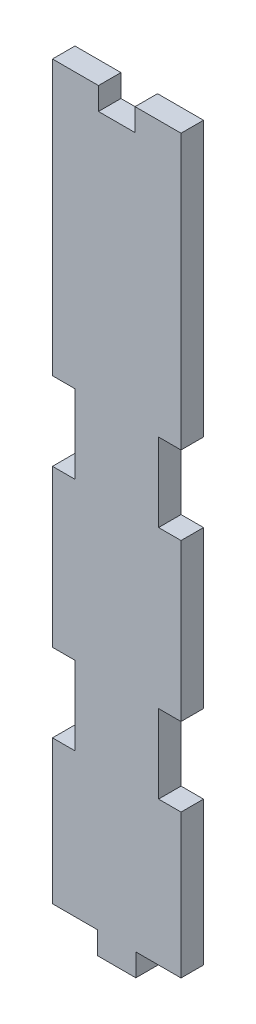
SolidWorks part; units mm, degrees
ref_plane "Front Plane" through (0, 0, 0) normal (0, 0, 1) x (1, 0, 0)
ref_plane "Top Plane" through (0, 0, 0) normal (0, 1, 0) x (1, 0, 0)
ref_plane "Right Plane" through (0, 0, 0) normal (1, 0, 0) x (0, 0, -1)
sketch "Sketch1" plane through (0, 0, 0) normal (0, 0, 1) x (1, 0, 0)
  line L0 (3.5, 70) -> (12.3, 70)
  line L1 (-12.3, -70) -> (-3.65, -70)
  line L2 (-12.3, -70) -> (-12.3, -42.5)
  line L3 (-12.3, 70) -> (-3.5, 70)
  line L4 (12.3, -70) -> (12.3, -42.5)
  line L5 (-12.3, -70) -> (12.3, 70) construction
  line L6 (-12.3, 70) -> (12.3, -70) construction
  line L8 (-3.5, 70) -> (-3.5, 65.7)
  line L9 (-3.5, 65.7) -> (3.5, 65.7)
  line L10 (3.5, 70) -> (3.5, 65.7)
  line L11 (3.65, -70) -> (12.3, -70)
  line L13 (-3.65, -70) -> (-3.65, -74.3)
  line L14 (-3.65, -74.3) -> (3.65, -74.3)
  line L15 (3.65, -70) -> (3.65, -74.3)
  line L16 (0, -74.3) -> (0, 65.7) construction
  line L17 (12.3, -27.5) -> (12.3, 2.5)
  line L18 (12.3, -27.5) -> (8, -27.5)
  line L20 (12.3, -42.5) -> (8, -42.5)
  line L21 (8, -27.5) -> (8, -42.5)
  line L22 (12.3, 17.5) -> (8, 17.5)
  line L24 (12.3, 2.5) -> (8, 2.5)
  line L25 (8, 17.5) -> (8, 2.5)
  line L26 (12.3, 17.5) -> (12.3, 70)
  line L27 (-8, 17.5) -> (-8, 2.5)
  line L28 (-12.3, 2.5) -> (-8, 2.5)
  line L29 (-12.3, 17.5) -> (-8, 17.5)
  line L30 (-8, -27.5) -> (-8, -42.5)
  line L31 (-12.3, -42.5) -> (-8, -42.5)
  line L32 (-12.3, -27.5) -> (-8, -27.5)
  line L33 (-12.3, 17.5) -> (-12.3, 70)
  line L34 (-12.3, -27.5) -> (-12.3, 2.5)
  point P0 (0, 0)
  point P10 (0, 65.7)
  point P15 (0, -74.3)
  point P26 (8, -35)
  point P27 (8, 10)
  dimension "D1" = 24.6
  dimension "D2" = 140
  dimension "D3" = 7
  dimension "D4" = 4.3
  dimension "D5" = 7.3
  dimension "D6" = 4.3
  dimension "D7" = 35
  dimension "D8" = 80
  dimension "D9" = 15
  dimension "D10" = 15
  dimension "D11" = 4.3
extrude "Boss-Extrude1" add sketch "Sketch1" along normal blind 4.3
